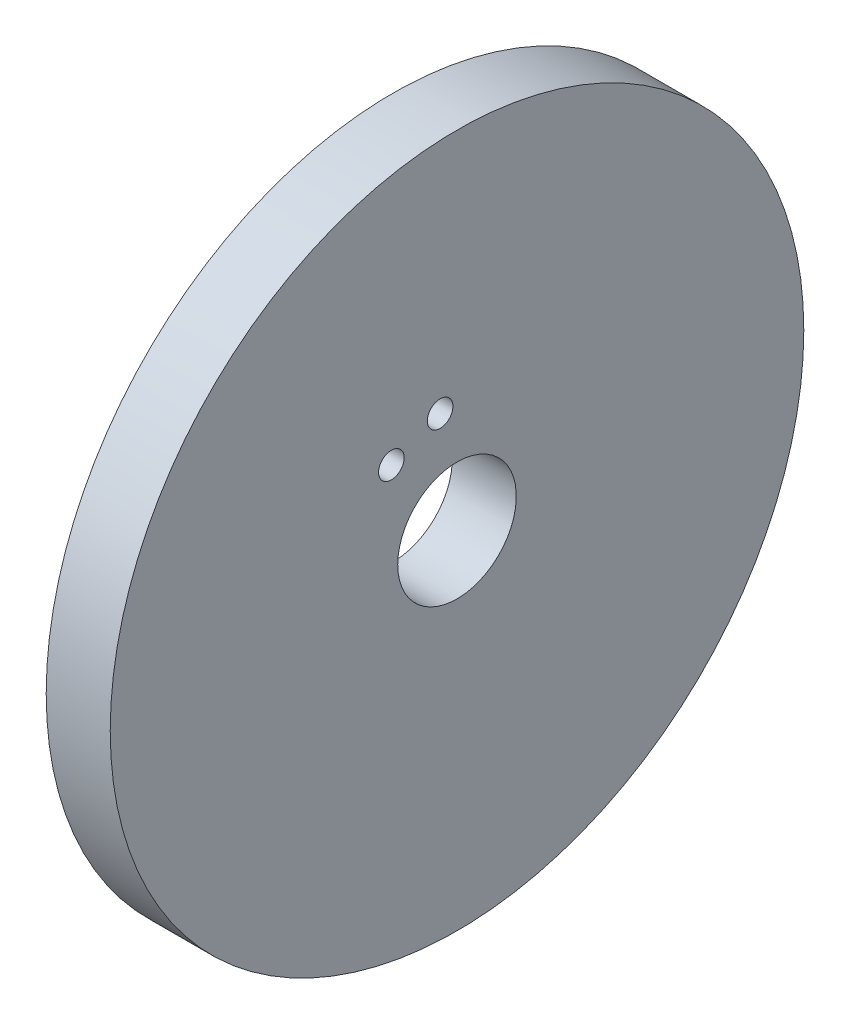
SolidWorks part; units mm, degrees
material "AISI 304"
ref_plane "Front Plane" through (0, 0, 0) normal (0, 0, 1) x (1, 0, 0)
ref_plane "Top Plane" through (0, 0, 0) normal (0, 1, 0) x (1, 0, 0)
ref_plane "Right Plane" through (0, 0, 0) normal (1, 0, 0) x (0, 0, -1)
sketch "Axial profile (mm)" plane through (0, 0, 0) normal (0, 0, 1) x (1, 0, 0)
  line L0 (-110, 0) -> (75, 0) construction
  line L1 (13.7, 11.1125) -> (25.7, 11.1125)
  line L2 (25.7, 11.1125) -> (25.7, 65)
  line L3 (25.7, 65) -> (13.7, 65)
  line L4 (13.7, 65) -> (13.7, 11.1125)
revolve "Full revolution" add sketch "Axial profile (mm)" angle 360 about L0
sketch "Sketch2" plane through (0, 0, 0) normal (1, 0, 0) x (0, 0, -1)
  circle A0 centre (-3.1638, 20.558) radius 2.4
  circle A1 centre (-12.2995, 16.7738) radius 2.4
extrude "Axial holes" cut sketch "Sketch2" along normal through all and the other way through all
sketch "Sketch3" plane through (0, 0, 0) normal (1, 0, 0) x (0, 0, -1)
  circle A0 centre (-31.8198, 31.8198) radius 1.25
  circle A1 centre (-31.8198, -31.8198) radius 1.25
  circle A2 centre (31.8198, -31.8198) radius 1.25
  circle A3 centre (31.8198, 31.8198) radius 1.25
extrude "Cut-Extrude2" cut sketch "Sketch3" along normal blind 7 from offset 13.7
